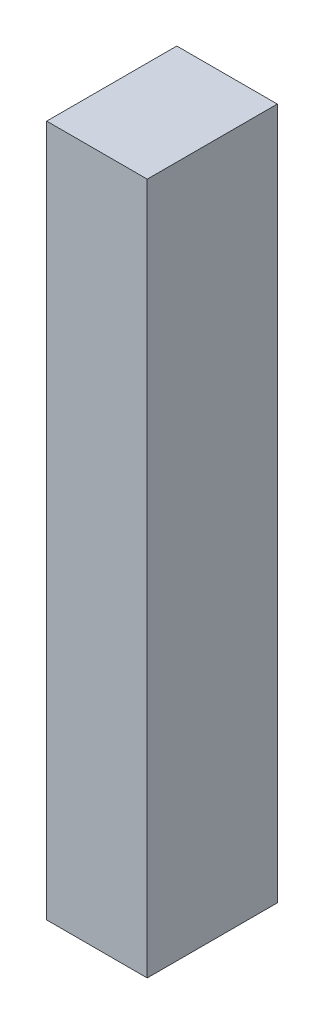
SolidWorks part; units mm, degrees
material "ABS"
ref_plane "Front Plane" through (0, 0, 0) normal (0, 0, 1) x (1, 0, 0)
ref_plane "Top Plane" through (0, 0, 0) normal (0, 1, 0) x (1, 0, 0)
ref_plane "Right Plane" through (0, 0, 0) normal (1, 0, 0) x (0, 0, -1)
sketch "Sketch1" plane through (0, 0, 0) normal (0, 1, 0) x (1, 0, 0)
  line L1 (0, 0) -> (17, 0)
  line L2 (0, 0) -> (0, 22)
  line L3 (0, 22) -> (17, 22)
  line L4 (17, 0) -> (17, 22)
  dimension "D1" = 22
  dimension "D2" = 17
extrude "Boss-Extrude1" add sketch "Sketch1" along normal blind 117
